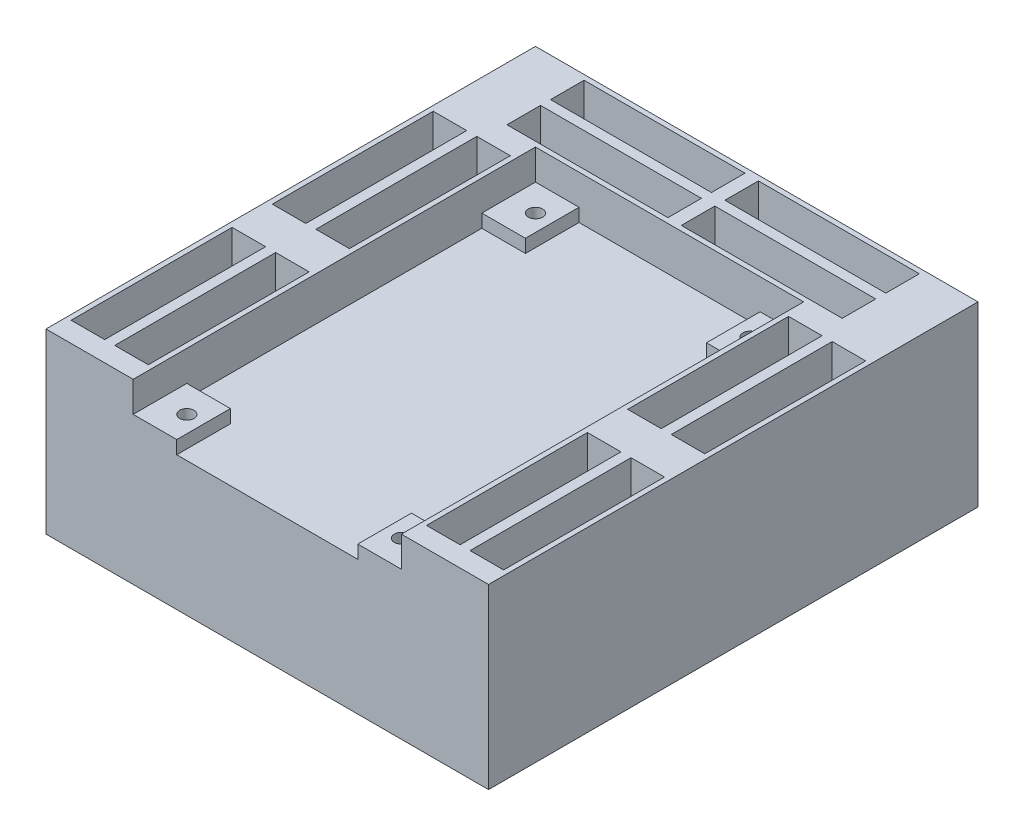
SolidWorks part; units mm, degrees
ref_plane "Front Plane" through (0, 0, 0) normal (0, 0, 1) x (1, 0, 0)
ref_plane "Top Plane" through (0, 0, 0) normal (0, 1, 0) x (1, 0, 0)
ref_plane "Right Plane" through (0, 0, 0) normal (1, 0, 0) x (0, 0, -1)
sketch "Sketch2" plane through (0, 0, 0) normal (0, 0, 1) x (1, 0, 0)
  line L0 (0, 0) -> (41.91, 0)
  line L1 (41.91, 0) -> (41.91, 33.655)
  line L2 (41.91, 33.655) -> (25.4, 33.655)
  line L3 (25.4, 33.655) -> (25.4, 27.9)
  line L4 (17.145, 25.4) -> (0, 25.4)
  line L5 (0, 25.4) -> (0, 0)
  line L6 (25.4, 27.9) -> (17.145, 27.9)
  line L7 (17.145, 27.9) -> (17.145, 25.4)
  dimension "D1" = 25.4
  dimension "D2" = 16.51
  dimension "D3" = 33.655
  dimension "D4" = 8.255
  dimension "D5" = 2.5
  dimension "D6" = 8.255
extrude "Boss-Extrude1" add sketch "Sketch2" against normal blind 76.2
sketch "Sketch3" plane through (0, 33.655, 0) normal (0, 1, 0) x (1, 0, 0)
  line L1 (26.3525, 3.81) -> (32.7025, 3.81)
  line L2 (26.3525, 3.81) -> (26.3525, 34.29)
  line L3 (26.3525, 34.29) -> (32.7025, 34.29)
  line L4 (32.7025, 3.81) -> (32.7025, 34.29)
  line L5 (25.4, 76.2) -> (25.4, 0) construction
  line L6 (26.3525, 34.29) -> (32.7025, 3.81) construction
  line L7 (26.3525, 3.81) -> (32.7025, 34.29) construction
  line L8 (41.91, 0) -> (25.4, 0) construction
  line L9 (26.3525, 41.91) -> (26.3525, 72.39)
  line L10 (26.3525, 41.91) -> (32.7025, 41.91)
  line L11 (32.7025, 41.91) -> (32.7025, 72.39)
  line L12 (26.3525, 72.39) -> (32.7025, 72.39)
  point P4 (29.5275, 19.05)
  dimension "D1" = 6.35
  dimension "D2" = 0.9525
  dimension "D3" = 30.48
  dimension "D4" = 19.05
  dimension "D5" = 2
extrude "Cut-Extrude1" cut sketch "Sketch3" against normal blind 31.75
pattern_linear "LPattern11" count 2 spacing 8.255 along (1, 0, 0) of "Cut-Extrude1"
sketch "Sketch4" plane through (0, 0, -76.2) normal (0, 0, -1) x (-1, 0, 0)
  line L1 (-41.91, 33.655) -> (0, 33.655)
  line L2 (-41.91, 33.655) -> (-41.91, 0)
  line L3 (-41.91, 0) -> (0, 0)
  line L4 (0, 33.655) -> (0, 0)
extrude "Boss-Extrude2" add sketch "Sketch4" along normal blind 16.51
sketch "Sketch5" plane through (0, 33.655, 0) normal (0, 1, 0) x (1, 0, 0)
  line L0 (0, 76.2) -> (25.4, 76.2) construction
  line L1 (31.75, 83.5025) -> (1.27, 83.5025)
  line L2 (31.75, 83.5025) -> (31.75, 77.1525)
  line L3 (31.75, 77.1525) -> (1.27, 77.1525)
  line L4 (1.27, 83.5025) -> (1.27, 77.1525)
  line L5 (1.27, 83.5025) -> (31.75, 77.1525) construction
  line L6 (31.75, 83.5025) -> (1.27, 77.1525) construction
  line L7 (25.4, 76.2) -> (25.4, 0) construction
  line L8 (32.7025, 72.39) -> (26.3525, 72.39) construction
  line L9 (26.3525, 41.91) -> (32.7025, 41.91) construction
  point P6 (16.51, 80.3275)
  dimension "D1" = 6.35
  dimension "D2" = 0.9525
  dimension "D3" = 8.89
  dimension "D4" = 30.48
  dimension "D5" = 30.48
extrude "Cut-Extrude2" cut sketch "Sketch5" against normal up to surface (31.75 mm away) up to face at (29.5275, 1.905, -57.15)
sketch "Sketch6" plane through (0, 27.9, 0) normal (0, 1, 0) x (1, 0, 0)
  line L2 (25.4, 76.2) -> (25.4, 0) construction
  line L3 (17.145, 0) -> (0, 0) construction
  circle A1 centre (20.32, 5.08) radius 1.35
  circle A2 centre (20.32, 71.12) radius 1.35
  dimension "D1" = 2.7
  dimension "D2" = 2
  dimension "D3" = 5.08
  dimension "D4" = 5.08
extrude "Cut-Extrude3" cut sketch "Sketch6" against normal blind 5
sketch "Sketch9" plane through (0, 27.9, 0) normal (0, 1, 0) x (1, 0, 0)
  line L0 (25.4, 76.2) -> (25.4, 0) construction
  line L1 (25.4, 66.04) -> (17.145, 66.04)
  line L2 (25.4, 66.04) -> (25.4, 10.16)
  line L3 (25.4, 10.16) -> (17.145, 10.16)
  line L4 (17.145, 66.04) -> (17.145, 10.16)
  line L5 (17.145, 76.2) -> (17.145, 0) construction
  line L6 (0, 76.2) -> (25.4, 76.2) construction
  line L7 (25.4, 0) -> (17.145, 0) construction
  dimension "D1" = 10.16
  dimension "D2" = 10.16
extrude "Cut-Extrude5" cut sketch "Sketch9" against normal up to surface (2.5 mm away) up to face at (8.5725, 25.4, -38.1)
pattern_linear "LPattern12" count 2 spacing 8.255 along (0, 0, -1) of "Cut-Extrude2"
mirror "Mirror3" about plane through (0, 25.4, -76.2) normal (-1, 0, 0) of "Boss-Extrude1", "Cut-Extrude1", "LPattern11", "Boss-Extrude2", "Cut-Extrude2", "Cut-Extrude3", "Cut-Extrude5", "LPattern12"
